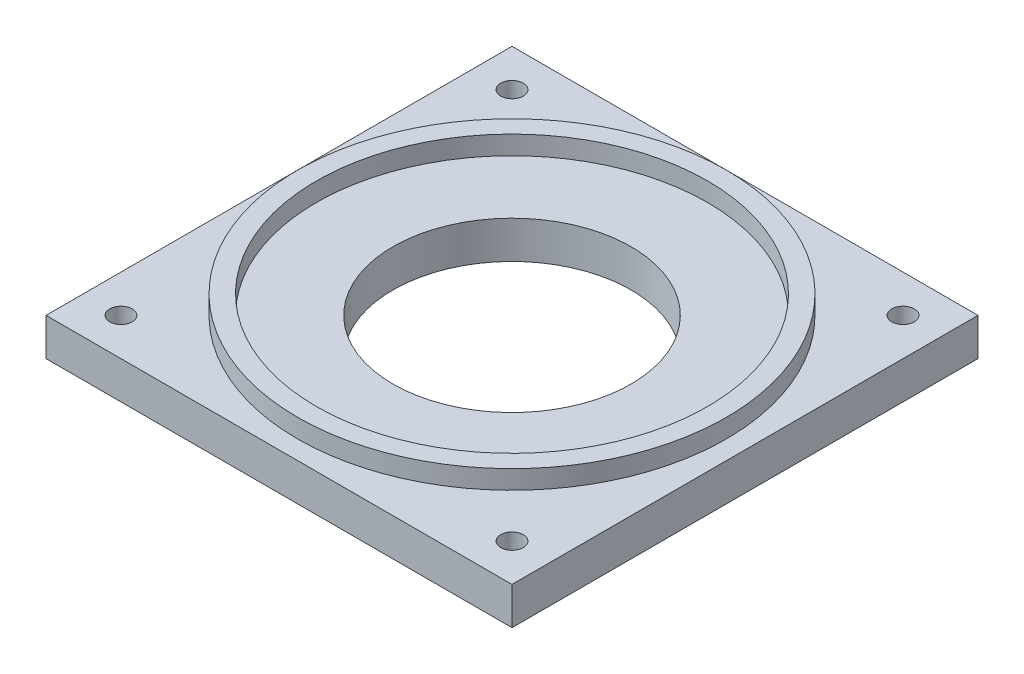
SolidWorks part; units mm, degrees
ref_plane "Front Plane" through (0, 0, 0) normal (0, 0, 1) x (1, 0, 0)
ref_plane "Top Plane" through (0, 0, 0) normal (0, 1, 0) x (1, 0, 0)
ref_plane "Right Plane" through (0, 0, 0) normal (1, 0, 0) x (0, 0, -1)
sketch "Sketch1" plane through (0, 0, 0) normal (0, 1, 0) x (1, 0, 0)
  line L1 (-31.075, 31.075) -> (31.075, 31.075)
  line L2 (-31.075, 31.075) -> (-31.075, -31.075)
  line L3 (-31.075, -31.075) -> (31.075, -31.075)
  line L4 (31.075, 31.075) -> (31.075, -31.075)
  line L5 (-31.075, 31.075) -> (31.075, -31.075) construction
  line L6 (-31.075, -31.075) -> (31.075, 31.075) construction
  point P0 (0, 0)
  dimension "D1" = 62.15
  dimension "D2" = 62.15
extrude "Boss-Extrude1" add sketch "Sketch1" along normal blind 5
sketch "Sketch2" plane through (0, 5, 0) normal (0, 1, 0) x (1, 0, 0)
  line L0 (-31.075, 31.075) -> (-31.075, -31.075) construction
  line L1 (31.075, 31.075) -> (-31.075, 31.075) construction
  line L2 (0, 31.075) -> (0, -31.075) construction
  line L3 (-31.075, -31.075) -> (31.075, -31.075) construction
  line L4 (-31.075, 0) -> (31.075, 0) construction
  line L5 (31.075, -31.075) -> (31.075, 31.075) construction
  circle A0 centre (-26.075, 26.075) radius 1.5
  circle A1 centre (-26.075, -26.075) radius 1.5
  circle A2 centre (26.075, -26.075) radius 1.5
  circle A3 centre (26.075, 26.075) radius 1.5
  dimension "D1" = 3
  dimension "D2" = 5
  dimension "D3" = 5
extrude "Cut-Extrude1" cut sketch "Sketch2" against normal up to next
sketch "Sketch3" plane through (0, 5, 0) normal (0, 1, 0) x (1, 0, 0)
  circle A0 centre (0, 0) radius 26.075
  circle A1 centre (0, 0) radius 28.575
  dimension "D1" = 52.15
  dimension "D2" = 57.15
extrude "Boss-Extrude2" add sketch "Sketch3" along normal blind 2.5
sketch "Sketch4" plane through (0, 5, 0) normal (0, 1, 0) x (1, 0, 0)
  circle A0 centre (0, 0) radius 15.875
  dimension "D1" = 31.75
extrude "Cut-Extrude2" cut sketch "Sketch4" against normal up to next
sketch "Sketch5" plane through (0, 0, 0) normal (0, -1, 0) x (1, 0, 0)
  line L0 (0, 31.075) -> (0, -31.075) construction
  line L1 (-31.075, 31.075) -> (31.075, 31.075) construction
  line L2 (31.075, -31.075) -> (-31.075, -31.075) construction
  line L3 (-31.075, 0) -> (31.075, 0) construction
  line L4 (-31.075, -31.075) -> (-31.075, 31.075) construction
  line L5 (31.075, 31.075) -> (31.075, -31.075) construction
  circle A0 centre (-26.075, 26.075) radius 3
  circle A1 centre (-26.075, -26.075) radius 3
  circle A2 centre (26.075, -26.075) radius 3
  circle A3 centre (26.075, 26.075) radius 3
  dimension "D1" = 6
extrude "Cut-Extrude3" cut sketch "Sketch5" against normal blind 2
equation "\"D2@Sketch1\"=\"D1@Sketch1\""
